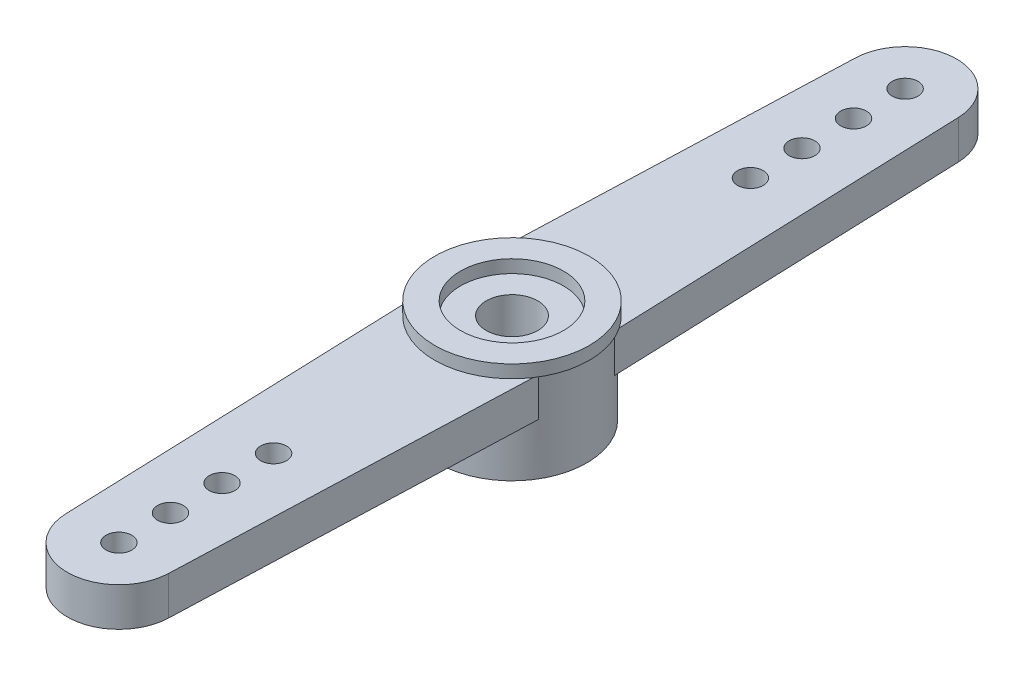
SolidWorks part; units mm, degrees
ref_plane "Plan de face" through (0, 0, 0) normal (0, 0, 1) x (1, 0, 0)
ref_plane "Plan de dessus" through (0, 0, 0) normal (0, 1, 0) x (1, 0, 0)
ref_plane "Plan de droite" through (0, 0, 0) normal (1, 0, 0) x (0, 0, -1)
sketch "Esquisse1" plane through (0, 0, 0) normal (0, 1, 0) x (1, 0, 0)
  circle A0 centre (0, 0) radius 2.9
  circle A1 centre (0, 0) radius 2
  dimension "D1" = 5.8
  dimension "D2" = 4
extrude "Boss.-Extru.1" add sketch "Esquisse1" against normal blind 2
sketch "Esquisse2" plane through (0, 0, 0) normal (0, 1, 0) x (1, 0, 0)
  line L0 (0, 15.25) -> (0, 0) construction
  line L1 (-1.9987, 15.3223) -> (-2.5, 1.4697)
  line L2 (1.9987, 15.3223) -> (2.5, 1.4697)
  circle A0 centre (0, 0) radius 17.25 construction
  arc A1 (1.9987, 15.3223) -> (-1.9987, 15.3223) centre (0, 15.25) ccw
  circle A2 centre (0, 0) radius 2.9 construction
  arc A3 (-2.5, 1.4697) -> (2.5, 1.4697) centre (0, 0) ccw
  circle A7 centre (0, 0) radius 1
  dimension "D1" = 34.5
  dimension "D2" = 4
  dimension "D7" = 2
  dimension "D3" = 5
extrude "Boss.-Extru.2" add sketch "Esquisse2" along normal blind 1.5
sketch "Esquisse4" plane through (0, 1.5, 0) normal (0, 1, 0) x (1, 0, 0)
  circle A0 centre (0, 15.25) radius 0.5
  dimension "D1" = 1
extrude "Enlèv. mat.-Extru.1" cut sketch "Esquisse4" against normal through all
pattern_linear "Répétition linéaire1" count 4 spacing 2 along (0, 0, 1) of "Enlèv. mat.-Extru.1"
pattern_circular "Répétition circulaire1" count 2 over 360 about axis through (0, 0, 0) along (0, 1, 0) of "Boss.-Extru.2", "Enlèv. mat.-Extru.1", "Répétition linéaire1"
sketch "Esquisse8" [suppressed] plane through (0, 1.5, 0) normal (0, 1, 0) x (1, 0, 0)
  circle A0 centre (0, 0) radius 2.9
  circle A1 centre (0, 0) radius 8.95
  circle A2 centre (0, 0) radius 8.95 construction
  arc A3 (-2.5, 1.4697) -> (2.5, 1.4697) centre (0, 0) ccw construction
extrude "Enlèv. mat.-Extru.2" [suppressed] cut sketch "Esquisse8" against normal through all
sketch "Esquisse3" plane through (0, 1.5, 0) normal (0, 1, 0) x (1, 0, 0)
  circle A0 centre (0, 0) radius 3
  circle A1 centre (0, 0) radius 2
  dimension "D1" = 6
  dimension "D2" = 4
extrude "Boss.-Extru.3" add sketch "Esquisse3" along normal blind 0.5
sketch "Esquisse7" [suppressed] plane through (0, 0, 0) normal (0, 1, 0) x (1, 0, 0)
  circle A0 centre (0, 0) radius 8.95 construction
  circle A1 centre (0, 0) radius 8.95
  circle A2 centre (0, 0) radius 3 construction
  circle A3 centre (0, 0) radius 3
extrude "Boss.-Extru.7" [suppressed] add sketch "Esquisse7" along normal blind 1.5 separate body
sketch "Esquisse9" [suppressed] plane through (0, 1.5, 0) normal (0, 1, 0) x (1, 0, 0)
  circle A0 centre (0, 0) radius 7.5 construction
  circle A1 centre (0, 7.5) radius 0.75
  circle A2 centre (2.9394, 6.9) radius 0.5
  circle A3 centre (5.4085, 5.196) radius 0.4
  dimension "D1" = 15
  dimension "D2" = 1.5
  dimension "D3" = 1
  dimension "D4" = 3
  dimension "D5" = 0.8
  dimension "D6" = 3
extrude "Enlèv. mat.-Extru.3" [suppressed] cut sketch "Esquisse9" against normal through all
pattern_circular "Répétition circulaire2" [suppressed] count 2 over 360
sketch "Esquisse10" [suppressed] plane through (0, 1.5, 0) normal (0, 1, 0) x (1, 0, 0)
  line L0 (-4.1568, 4.3268) -> (4.1568, -4.3268) construction
  line L1 (2.9394, 6.9) -> (-2.9394, -6.9) construction
  line L2 (5.4085, 5.196) -> (-5.4085, -5.196) construction
  line L3 (-5.52, 2.3515) -> (5.52, -2.3515) construction
  circle A0 centre (0, 0) radius 6 construction
  circle A1 centre (5.52, -2.3515) radius 0.5
  circle A2 centre (-5.52, 2.3515) radius 0.5
  circle A3 centre (-4.1568, 4.3268) radius 0.4
  circle A4 centre (4.1568, -4.3268) radius 0.4
  circle A5 centre (2.9394, 6.9) radius 0.5 construction
  circle A6 centre (5.4085, 5.196) radius 0.4 construction
  dimension "D1" = 12
extrude "Enlèv. mat.-Extru.4" [suppressed] cut sketch "Esquisse10" against normal through all
